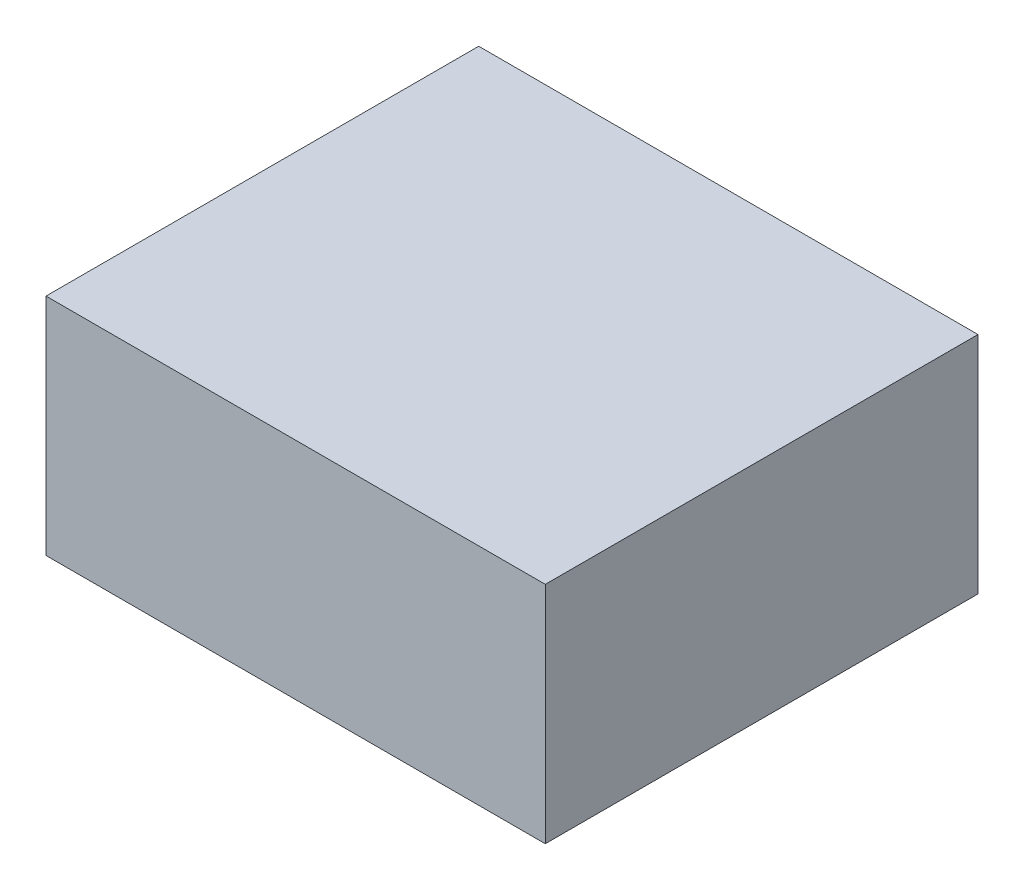
SolidWorks part; units mm, degrees
ref_plane "Front Plane" through (0, 0, 0) normal (0, 0, 1) x (1, 0, 0)
ref_plane "Top Plane" through (0, 0, 0) normal (0, 1, 0) x (1, 0, 0)
ref_plane "Right Plane" through (0, 0, 0) normal (1, 0, 0) x (0, 0, -1)
sketch "Sketch1" plane through (0, 0, 0) normal (0, 1, 0) x (1, 0, 0)
  line L1 (-30, -26) -> (30, -26)
  line L2 (-30, -26) -> (-30, 26)
  line L3 (-30, 26) -> (30, 26)
  line L4 (30, -26) -> (30, 26)
  line L5 (-30, -26) -> (30, 26) construction
  line L6 (-30, 26) -> (30, -26) construction
  point P0 (0, 0)
  dimension "D1" = 60
  dimension "D2" = 52
extrude "Boss-Extrude1" add sketch "Sketch1" along normal blind 27
